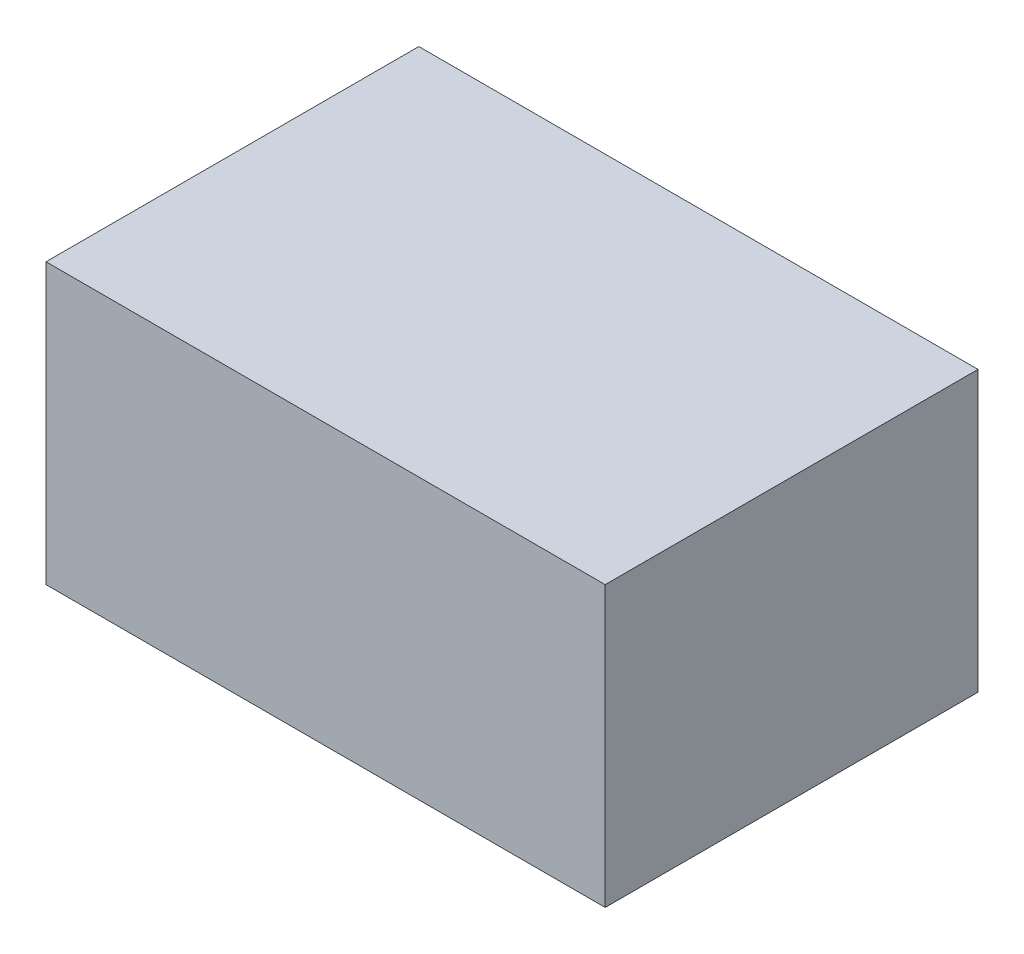
SolidWorks part; units mm, degrees
ref_plane "Спереди" through (0, 0, 0) normal (0, 0, 1) x (1, 0, 0)
ref_plane "Сверху" through (0, 0, 0) normal (0, 1, 0) x (1, 0, 0)
ref_plane "Справа" through (0, 0, 0) normal (1, 0, 0) x (0, 0, -1)
sketch "Эскиз1" plane through (0, 0, 0) normal (0, 1, 0) x (1, 0, 0)
  line L1 (0, 0) -> (120, 0)
  line L2 (0, 0) -> (0, 80)
  line L3 (0, 80) -> (120, 80)
  line L4 (120, 0) -> (120, 80)
  dimension "D1" = 120
  dimension "D2" = 80
extrude "Бобышка-Вытянуть1" add sketch "Эскиз1" along normal blind 60
shell "Оболочка1" thickness 5
sketch "Эскиз2" [suppressed] plane through (0, 0, 0) normal (0, 1, 0) x (1, 0, 0)
  line L0 (5, 75) -> (115, 5)
  line L1 (115, 75) -> (5, 5)
  line L2 (60, 5) -> (60, 75)
  line L3 (5, 5) -> (115, 5) construction
  line L4 (115, 75) -> (5, 75) construction
  line L5 (5, 40) -> (115, 40)
  line L6 (5, 75) -> (5, 5) construction
  line L7 (115, 5) -> (115, 75) construction
ref_plane "Плоскость1" through (0, 0, -40) normal (0, 0, 1) x (1, 0, 0)
sketch "Эскиз3" [suppressed] plane through (0, 0, -40) normal (0, 0, 1) x (1, 0, 0)
  line L0 (0, 60) -> (30, 100)
  line L1 (30, 100) -> (80, 100)
  line L2 (80, 100) -> (120, 60)
